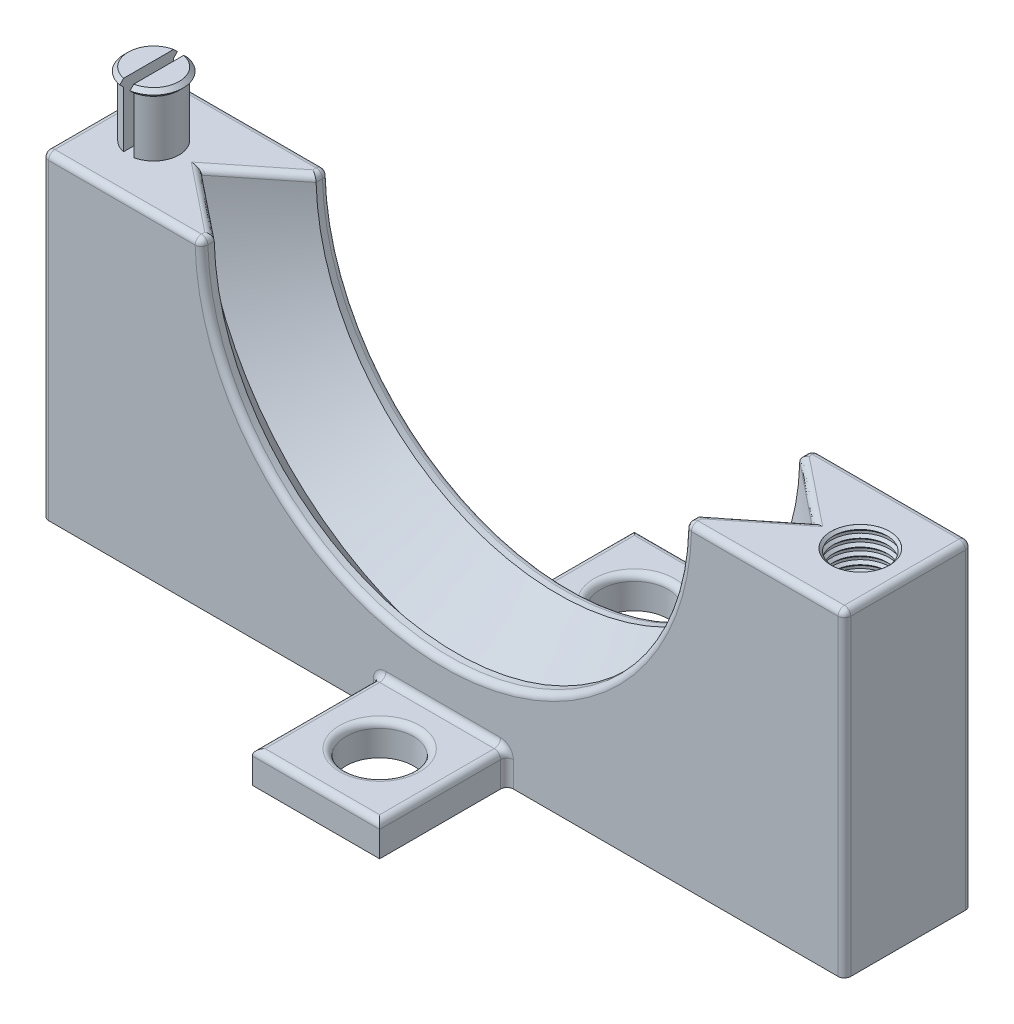
SolidWorks part; units mm, degrees
ref_plane "Front Plane" through (0, 0, 0) normal (0, 0, 1) x (1, 0, 0)
ref_plane "Top Plane" through (0, 0, 0) normal (0, 1, 0) x (1, 0, 0)
ref_plane "Right Plane" through (0, 0, 0) normal (1, 0, 0) x (0, 0, -1)
sketch "Sketch1" plane through (0, 0, 0) normal (0, 0, 1) x (1, 0, 0)
  line L0 (-40.005, 0) -> (40.005, 0)
  line L1 (40.005, 0) -> (40.005, 31.75)
  line L2 (40.005, 31.75) -> (24.13, 31.75)
  line L3 (-24.13, 31.75) -> (-40.005, 31.75)
  line L4 (-40.005, 31.75) -> (-40.005, 0)
  arc A0 (24.13, 31.75) -> (-24.13, 31.75) centre (0, 31.75) cw
  point P7 (0, 0)
  dimension "D2" = 24.13
  dimension "D1" = 31.75
  dimension "D3" = 15.875
extrude "Boss-Extrude1" add sketch "Sketch1" along normal blind 12.7
sketch "Sketch2" plane through (0, 31.75, 0) normal (0, 1, 0) x (1, 0, 0)
  line L0 (24.13, -11.43) -> (30.48, -6.35)
  line L2 (24.13, -12.7) -> (24.13, 0) construction
  line L3 (30.48, -6.35) -> (24.13, -1.27)
  line L4 (22.8654, -6.35) -> (40.005, -6.35) construction
  line L5 (24.13, -1.27) -> (24.13, -11.43)
  line L6 (40.005, -12.7) -> (40.005, 0) construction
  line L7 (0, 0) -> (0, -23.6383) construction
  dimension "D1" = 10.16
  dimension "D2" = 6.35
revolve "Cut-Revolve1" cut sketch "Sketch2" angle 360 about L7
sketch "Sketch6" plane through (0, 31.75, 0) normal (0, 1, 0) x (1, 0, 0)
  line L0 (30.48, -6.35) -> (40.005, -6.35) construction
  line L1 (40.005, -12.7) -> (40.005, 0) construction
  circle A0 centre (35.2425, -6.35) radius 2.921
  dimension "D1" = 5.842
extrude "Cut-Extrude2" cut sketch "Sketch6" against normal blind 9.525
sketch "Sketch11" plane through (0, 31.75, 0) normal (0, 1, 0) x (1, 0, 0)
  line L0 (30.48, -6.35) -> (40.005, -6.35) construction
  line L1 (40.005, -12.7) -> (40.005, 0) construction
ref_plane "Plane1" through (0, 0, 6.35) normal (0, 0, 1) x (1, 0, 0)
sketch "Sketch15" plane through (0, 0, 6.35) normal (0, 0, 1) x (1, 0, 0)
  line L0 (-37.7825, 31.75) -> (-37.7825, 37.338)
  line L1 (-24.13, 31.75) -> (-40.005, 31.75) construction
  line L2 (-37.7825, 37.338) -> (-38.1635, 37.719)
  line L3 (-38.1635, 37.719) -> (-37.7825, 38.1)
  line L4 (-37.7825, 38.1) -> (-35.2425, 38.1)
  line L5 (-35.2425, 38.1) -> (-35.2425, 31.75)
  line L6 (-35.2425, 31.75) -> (-37.7825, 31.75)
  line L7 (-40.005, 31.75) -> (-40.005, 0) construction
  line L8 (-37.7825, 38.1) -> (-37.7825, 37.338) construction
  line L9 (-30.48, 31.75) -> (-40.005, 31.75) construction
  dimension "D1" = 2.54
  dimension "D3" = 6.35
  dimension "D4" = 90
  dimension "D5" = 2.921
revolve "Revolve2" add sketch "Sketch15" angle 360 about L5
sketch "Sketch12" plane through (0, 0, 6.35) normal (0, 0, 1) x (1, 0, 0)
  line L0 (35.2425, 31.75) -> (35.2425, 26.6144) construction
  line L1 (30.48, 31.75) -> (40.005, 31.75) construction
  line L2 (32.3215, 30.48) -> (32.5755, 30.734)
  line L3 (32.3215, 31.242) -> (32.5755, 31.496)
  line L4 (32.5755, 31.496) -> (32.3215, 31.75)
  line L5 (32.3215, 31.75) -> (32.3215, 31.242)
  line L6 (35.2425, 31.75) -> (32.3215, 31.75) construction
  line L7 (32.5755, 30.734) -> (32.3215, 30.988)
  line L8 (32.3215, 30.988) -> (32.3215, 30.48)
  line L9 (32.3215, 29.718) -> (32.5755, 29.972)
  line L10 (32.5755, 29.972) -> (32.3215, 30.226)
  line L11 (32.3215, 30.226) -> (32.3215, 29.718)
  line L12 (32.3215, 28.956) -> (32.5755, 29.21)
  line L13 (32.5755, 29.21) -> (32.3215, 29.464)
  line L14 (32.3215, 29.464) -> (32.3215, 28.956)
  line L15 (32.3215, 28.194) -> (32.5755, 28.448)
  line L16 (32.5755, 28.448) -> (32.3215, 28.702)
  line L17 (32.3215, 28.702) -> (32.3215, 28.194)
  line L18 (32.3215, 27.432) -> (32.5755, 27.686)
  line L19 (32.5755, 27.686) -> (32.3215, 27.94)
  line L20 (32.3215, 27.94) -> (32.3215, 27.432)
  line L21 (32.3215, 26.67) -> (32.5755, 26.924)
  line L22 (32.5755, 26.924) -> (32.3215, 27.178)
  line L23 (32.3215, 27.178) -> (32.3215, 26.67)
  line L24 (32.3215, 25.908) -> (32.5755, 26.162)
  line L25 (32.5755, 26.162) -> (32.3215, 26.416)
  line L26 (32.3215, 26.416) -> (32.3215, 25.908)
  line L27 (32.3215, 25.146) -> (32.5755, 25.4)
  line L28 (32.5755, 25.4) -> (32.3215, 25.654)
  line L29 (32.3215, 25.654) -> (32.3215, 25.146)
  line L30 (32.3215, 24.384) -> (32.5755, 24.638)
  line L31 (32.5755, 24.638) -> (32.3215, 24.892)
  line L32 (32.3215, 24.892) -> (32.3215, 24.384)
  line L33 (32.3215, 23.622) -> (32.5755, 23.876)
  line L34 (32.5755, 23.876) -> (32.3215, 24.13)
  line L35 (32.3215, 24.13) -> (32.3215, 23.622)
  line L36 (32.3215, 22.86) -> (32.5755, 23.114)
  line L37 (32.5755, 23.114) -> (32.3215, 23.368)
  line L38 (32.3215, 23.368) -> (32.3215, 22.86)
  line L39 (32.3215, 22.098) -> (32.5755, 22.352)
  line L40 (32.5755, 22.352) -> (32.3215, 22.606)
  line L41 (32.3215, 22.606) -> (32.3215, 22.098)
  line L42 (32.3215, 21.336) -> (32.5755, 21.59)
  line L43 (32.5755, 21.59) -> (32.3215, 21.844)
  line L44 (32.3215, 21.844) -> (32.3215, 21.336)
  line L45 (32.3215, 20.574) -> (32.5755, 20.828)
  line L46 (32.5755, 20.828) -> (32.3215, 21.082)
  line L47 (32.3215, 21.082) -> (32.3215, 20.574)
  line L48 (32.3215, 19.812) -> (32.5755, 20.066)
  line L49 (32.5755, 20.066) -> (32.3215, 20.32)
  line L50 (32.3215, 20.32) -> (32.3215, 19.812)
  line L51 (32.3215, 19.05) -> (32.5755, 19.304)
  line L52 (32.5755, 19.304) -> (32.3215, 19.558)
  line L53 (32.3215, 19.558) -> (32.3215, 19.05)
  line L54 (32.3215, 18.288) -> (32.5755, 18.542)
  line L55 (32.5755, 18.542) -> (32.3215, 18.796)
  line L56 (32.3215, 18.796) -> (32.3215, 18.288)
  line L57 (32.3215, 17.526) -> (32.5755, 17.78)
  line L58 (32.5755, 17.78) -> (32.3215, 18.034)
  line L59 (32.3215, 18.034) -> (32.3215, 17.526)
  line L60 (32.3215, 16.764) -> (32.5755, 17.018)
  line L61 (32.5755, 17.018) -> (32.3215, 17.272)
  line L62 (32.3215, 17.272) -> (32.3215, 16.764)
  dimension "D1" = 2.921
  dimension "D2" = 0.508
  dimension "D3" = 90
  dimension "D4" = 20
revolve "Revolve1" add sketch "Sketch12" angle 360 about L0
sketch "Sketch16" plane through (0, 38.1, 0) normal (0, 1, 0) x (1, 0, 0)
  line L1 (-35.7505, -11.9418) -> (-34.7345, -11.9418)
  line L2 (-35.7505, -11.9418) -> (-35.7505, -0.7582)
  line L3 (-35.7505, -0.7582) -> (-34.7345, -0.7582)
  line L4 (-34.7345, -11.9418) -> (-34.7345, -0.7582)
  line L5 (-35.7505, -11.9418) -> (-34.7345, -0.7582) construction
  line L6 (-35.7505, -0.7582) -> (-34.7345, -11.9418) construction
  point P0 (-35.2425, -6.35)
  dimension "D1" = 1.016
extrude "Cut-Extrude3" cut sketch "Sketch16" against normal up to surface (6.35 mm away) up to face at (-35.2425, 31.75, 8.89)
sketch "Sketch17" plane through (0, 0, 0) normal (0, -1, 0) x (-1, 0, 0)
  line L0 (40.005, -6.35) -> (-40.005, -6.35) construction
  line L1 (40.005, -12.7) -> (40.005, 0) construction
  line L2 (-40.005, -12.7) -> (-40.005, 0) construction
  line L3 (-6.35, -12.7) -> (6.35, -12.7)
  line L4 (6.35, 12.7) -> (-6.35, 12.7)
  line L5 (6.35, 12.7) -> (6.35, 0)
  line L6 (6.35, -25.4) -> (-6.35, -25.4)
  line L7 (-6.35, 12.7) -> (-6.35, 0)
  line L8 (6.35, 12.7) -> (-6.35, -25.4) construction
  line L9 (6.35, -25.4) -> (-6.35, 12.7) construction
  line L10 (40.005, -12.7) -> (-40.005, -12.7) construction
  line L11 (-6.35, 0) -> (6.35, 0)
  line L12 (-6.35, -12.7) -> (-6.35, -25.4)
  line L13 (6.35, -12.7) -> (6.35, -25.4)
  point P6 (0, -6.35)
  dimension "D1" = 12.7
  dimension "D2" = 38.1
extrude "Boss-Extrude2" add sketch "Sketch17" against normal blind 3.175
sketch "Sketch18" plane through (0, 3.175, 0) normal (0, 1, 0) x (1, 0, 0)
  line L0 (0, -25.4) -> (0, 12.7) construction
  line L1 (6.35, -25.4) -> (-6.35, -25.4) construction
  line L2 (-6.35, 12.7) -> (6.35, 12.7) construction
  circle A0 centre (0, -19.05) radius 3.3655
  circle A1 centre (0, 6.35) radius 3.3655
  dimension "D3" = 6.731
  dimension "D4" = 6.731
  dimension "D1" = 25.4
  dimension "D2" = 6.35
extrude "Cut-Extrude4" cut sketch "Sketch18" against normal through all
fillet "Fillet1" radius 0.635 34 edges at (6.35, 3.175, -6.35) (0, 3.175, 25.4) (-6.35, 3.175, -6.35) (0, 3.175, 12.7) (0, 3.175, 22.4155) (0, 3.175, -12.7) (0, 3.175, 0) (0, 3.175, -2.9845) (40.005, 15.875, 0) (40.005, 15.875, 12.7) (0, 7.62, 0) (-24.13, 31.75, 0.635) (-24.13, 31.75, 12.065) (24.13, 31.75, 12.065) (24.13, 31.75, 0.635) (27.305, 31.75, 3.81) (27.305, 31.75, 8.89) (32.0675, 31.75, 12.7) (40.005, 31.75, 6.35) (32.0675, 31.75, 0) (-32.0675, 31.75, 0) (-27.305, 31.75, 3.81) (-27.305, 31.75, 8.89) (0, 7.62, 12.7) (-32.0675, 31.75, 12.7) (-40.005, 15.875, 12.7) (-40.005, 31.75, 6.35) (-40.005, 15.875, 0) (-6.35, 3.175, 19.05) (6.35, 3.175, 19.05)
